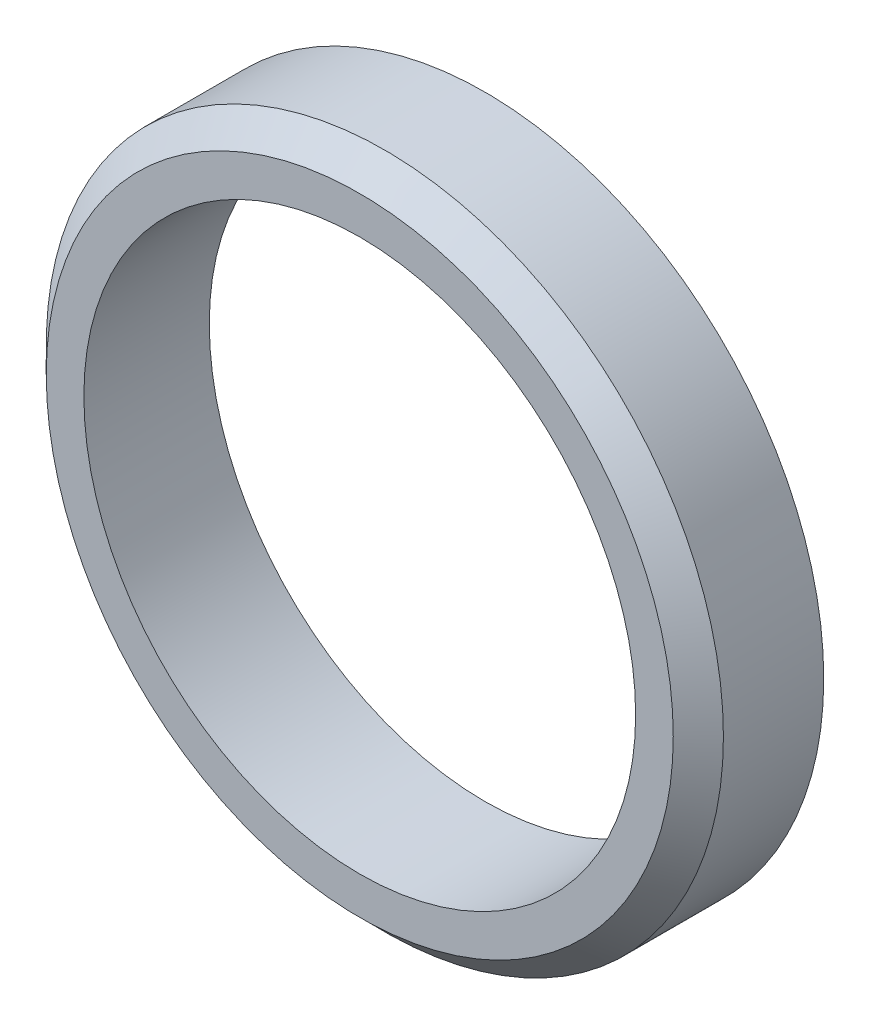
SolidWorks part; units mm, degrees
ref_plane "Спереди" through (0, 0, 0) normal (0, 0, 1) x (1, 0, 0)
ref_plane "Сверху" through (0, 0, 0) normal (0, 1, 0) x (1, 0, 0)
ref_plane "Справа" through (0, 0, 0) normal (1, 0, 0) x (0, 0, -1)
sketch "Эскиз1" plane through (0, 0, 0) normal (0, 0, 1) x (1, 0, 0)
  circle A0 centre (0, 0) radius 67.5
  dimension "D1" = 135
extrude "Бобышка-Вытянуть1" add sketch "Эскиз1" along normal blind 25
chamfer "Фаска1" distance 5 angle 45 1 edges at (67.5, 0, 25)
sketch "Эскиз2" plane through (0, 0, 0) normal (0, 0, -1) x (-1, 0, 0)
  circle A0 centre (0, 0) radius 55
  dimension "D1" = 110
extrude "Вырез-Вытянуть1" cut sketch "Эскиз2" against normal through all
